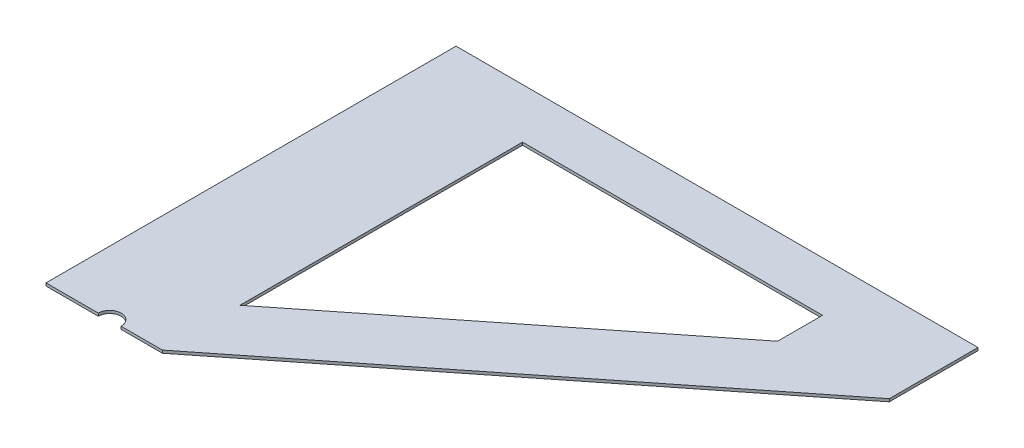
SolidWorks part; units mm, degrees
material "Custom Plastic"
ref_plane "X-Y Datum" through (0, 0, 0) normal (0, 0, 1) x (1, 0, 0)
ref_plane "X-Z Datum" through (0, 0, 0) normal (0, 1, 0) x (1, 0, 0)
ref_plane "Y-Z Datum" through (0, 0, 0) normal (1, 0, 0) x (0, 0, -1)
ref_plane "Plane1" through (0, 0, 0) normal (0, 1, 0) x (1, 0, 0)
sketch "Sketch1" plane through (0, 0, 0) normal (0, 1, 0) x (1, 0, 0)
  line L0 (525.1196, -749.3) -> (60.325, -1117.6)
  line L2 (-73.025, -647.7) -> (-73.025, -1117.6)
  line L3 (525.1196, -647.7) -> (525.1196, -749.3)
  line L4 (525.1196, -647.7) -> (-73.025, -647.7)
  line L5 (-73.025, -1117.6) -> (60.325, -1117.6)
  line L7 (60.325, -704.85) -> (60.325, -1028.7)
  line L8 (404.0768, -756.3134) -> (60.325, -1028.7)
  line L9 (404.0768, -756.3134) -> (404.0768, -704.85)
  line L10 (404.0768, -704.85) -> (60.325, -704.85)
  circle A0 centre (0, -1117.6) radius 13.081
  dimension "D5" = 26.162
  dimension "D1" = 598.1446
  dimension "D2" = 469.9
  dimension "D3" = 133.35
  dimension "D4" = 101.6
  dimension "D6" = 323.85
  dimension "D7" = 88.9
extrude "Boss-Extrude1" add sketch "Sketch1" along normal mid plane 3.175
